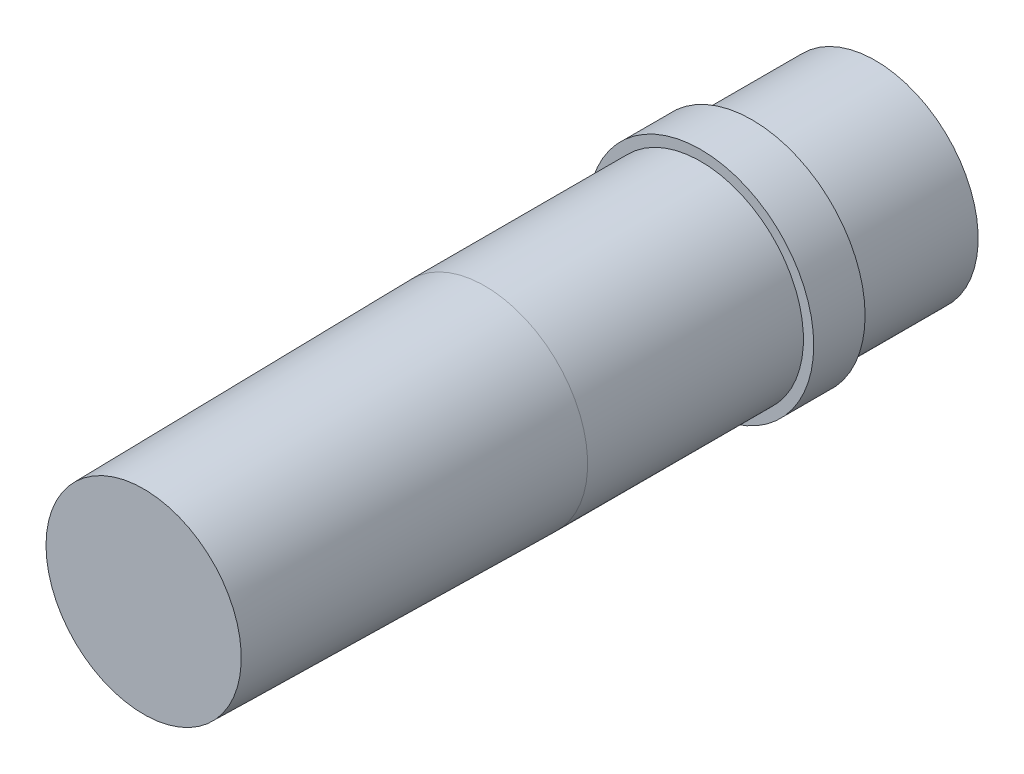
SolidWorks part; units mm, degrees
ref_plane "Front" through (0, 0, 0) normal (0, 0, 1) x (1, 0, 0)
ref_plane "Top" through (0, 0, 0) normal (0, 1, 0) x (1, 0, 0)
ref_plane "Right" through (0, 0, 0) normal (1, 0, 0) x (0, 0, -1)
sketch "Sketch1" plane through (0, 0, 0) normal (0, 1, 0) x (1, 0, 0)
  line L0 (0, 1.5998) -> (0, -1.3793) construction
  line L1 (0, 3.56) -> (-0.5, 3.56)
  line L2 (-0.5, 3.56) -> (-0.5, 2.96)
  line L3 (-0.5, 2.96) -> (-0.55, 2.96)
  line L4 (-0.55, 2.96) -> (-0.55, 2.71)
  line L5 (-0.55, 2.71) -> (-0.5, 2.71)
  line L6 (-0.5, 2.71) -> (-0.5, 1.66)
  line L7 (-0.475, 0) -> (0, 0)
  line L8 (-0.5, 1.66) -> (-0.475, 0)
  line L9 (0, 3.56) -> (0, 0)
  dimension "D1" = 0.5
  dimension "D2" = 3.56
  dimension "D3" = 0.475
  dimension "D4" = 1.9
  dimension "D5" = 0.55
  dimension "D6" = 0.25
  dimension "D7" = 0.6
revolve "Revolve1" add sketch "Sketch1" angle 360 about L0
sketch "Sketch2" plane through (0, 0, -3.56) normal (0, 0, -1) x (-1, 0, 0)
  circle A0 centre (0, 0) radius 0.425
  dimension "D1" = 0.85
extrude "Cut-Extrude1" cut sketch "Sketch2" against normal blind 1.5
